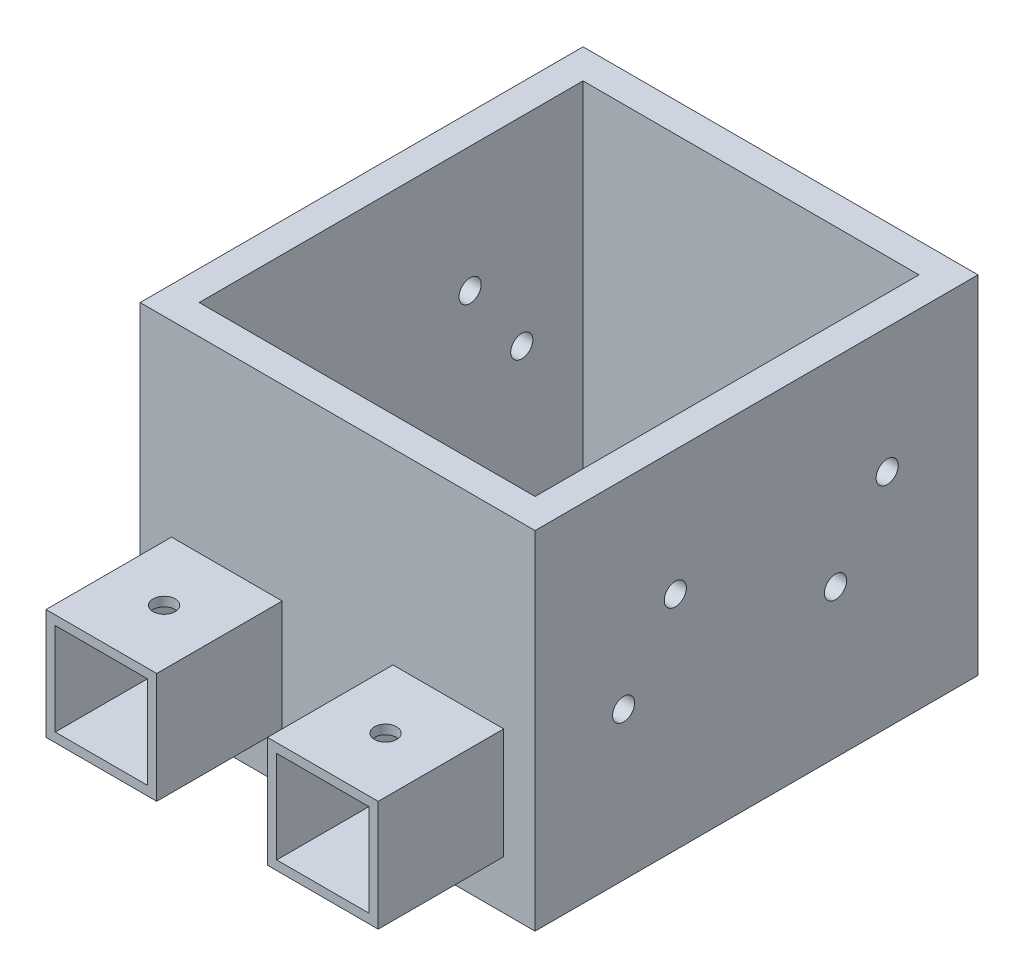
SolidWorks part; units mm, degrees
ref_plane "Front Plane" through (0, 0, 0) normal (0, 0, 1) x (1, 0, 0)
ref_plane "Top Plane" through (0, 0, 0) normal (0, 1, 0) x (1, 0, 0)
ref_plane "Right Plane" through (0, 0, 0) normal (1, 0, 0) x (0, 0, -1)
sketch "Sketch1" plane through (0, 0, 0) normal (0, 1, 0) x (1, 0, 0)
  line L1 (-26.75, 30) -> (26.75, 30)
  line L2 (-26.75, 30) -> (-26.75, -30)
  line L3 (-26.75, -30) -> (26.75, -30)
  line L4 (26.75, 30) -> (26.75, -30)
  line L5 (-26.75, 30) -> (26.75, -30) construction
  line L6 (-26.75, -30) -> (26.75, 30) construction
  line L7 (-22.75, 26) -> (22.75, 26)
  line L8 (-22.75, 26) -> (-22.75, -26)
  line L9 (-22.75, -26) -> (22.75, -26)
  line L10 (22.75, 26) -> (22.75, -26)
  line L11 (-22.75, 26) -> (22.75, -26) construction
  line L12 (-22.75, -26) -> (22.75, 26) construction
  point P0 (0, 0)
  point P6 (0, 0)
  dimension "D1" = 45.5
  dimension "D2" = 4
  dimension "D3" = 4
extrude "Boss-Extrude1" add sketch "Sketch1" along normal blind 47
sketch "Sketch3" plane through (-26.75, 0, 0) normal (-1, 0, 0) x (0, 0, 1)
  line L0 (-30, 47) -> (30, 47) construction
  circle A0 centre (18, 30.05) radius 1.5
  circle A1 centre (11, 20.05) radius 1.5
  dimension "D1" = 3
  dimension "D3" = 3
  dimension "D2" = 16.95
  dimension "D4" = 10
  dimension "D5" = 7
  dimension "D6" = 8
extrude "Cut-Extrude1" cut sketch "Sketch3" against normal blind 4 and the other way through all
pattern_linear "LPattern1" count 2 spacing 28.7 along (0, 0, -1) of "Cut-Extrude1"
sketch "Sketch4" plane through (26.75, 0, 0) normal (1, 0, 0) x (0, 0, -1)
  line L0 (-30, 47) -> (30, 47) construction
  circle A0 centre (-11, 30.05) radius 1.5
  circle A1 centre (-18, 20.05) radius 1.5
  dimension "D1" = 3
  dimension "D2" = 3
  dimension "D3" = 10
  dimension "D4" = 7
  dimension "D5" = 16.95
  dimension "D6" = 8
extrude "Cut-Extrude2" cut sketch "Sketch4" against normal blind 4
pattern_linear "LPattern2" count 2 spacing 28.7 along (0, 0, -1) of "Cut-Extrude2"
sketch "Sketch5" plane through (0, 0, 30) normal (0, 0, 1) x (1, 0, 0)
  line L0 (26.75, 47) -> (26.75, 0) construction
  line L1 (-22.5, 21.61) -> (-7.5, 21.61)
  line L2 (-22.5, 21.61) -> (-22.5, 6.61)
  line L3 (-22.5, 6.61) -> (-7.5, 6.61)
  line L4 (-7.5, 21.61) -> (-7.5, 6.61)
  line L5 (-22.5, 21.61) -> (-7.5, 6.61) construction
  line L6 (-22.5, 6.61) -> (-7.5, 21.61) construction
  line L7 (7.5, 21.61) -> (22.5, 21.61)
  line L8 (7.5, 21.61) -> (7.5, 6.61)
  line L9 (7.5, 6.61) -> (22.5, 6.61)
  line L10 (22.5, 21.61) -> (22.5, 6.61)
  line L11 (7.5, 21.61) -> (22.5, 6.61) construction
  line L12 (7.5, 6.61) -> (22.5, 21.61) construction
  line L13 (-26.75, 0) -> (26.75, 0) construction
  line L14 (-26.75, 47) -> (-26.75, 0) construction
  line L15 (8.75, 20.36) -> (21.25, 20.36)
  line L17 (8.75, 20.36) -> (8.75, 7.86)
  line L18 (8.75, 7.86) -> (21.25, 7.86)
  line L19 (21.25, 20.36) -> (21.25, 7.86)
  line L20 (8.75, 20.36) -> (21.25, 7.86) construction
  line L21 (8.75, 7.86) -> (21.25, 20.36) construction
  line L22 (-21.25, 20.36) -> (-8.75, 20.36)
  line L23 (-21.25, 20.36) -> (-21.25, 7.86)
  line L24 (-21.25, 7.86) -> (-8.75, 7.86)
  line L25 (-8.75, 20.36) -> (-8.75, 7.86)
  line L26 (-21.25, 20.36) -> (-8.75, 7.86) construction
  line L27 (-21.25, 7.86) -> (-8.75, 20.36) construction
  point P0 (-15, 14.11)
  point P5 (15, 14.11)
  point P16 (-15, 14.11)
  point P18 (15, 14.11)
  dimension "D1" = 4.25
  dimension "D2" = 4.25
  dimension "D3" = 15
  dimension "D5" = 12.5
  dimension "D4" = 6.61
extrude "Boss-Extrude2" add sketch "Sketch5" along normal blind 17
sketch "Sketch6" plane through (0, 21.61, 0) normal (0, 1, 0) x (1, 0, 0)
  line L1 (-7.5, -47) -> (-7.5, -30) construction
  line L2 (-7.5, -47) -> (-22.5, -47) construction
  line L3 (22.5, -47) -> (22.5, -30) construction
  line L4 (22.5, -47) -> (7.5, -47) construction
  circle A0 centre (-15, -38.5) radius 1.5
  circle A1 centre (15, -38.5) radius 1.5
  point P6 (-7.5, -38.5)
  point P11 (-15, -47)
  point P14 (22.5, -38.5)
  point P18 (15, -47)
  dimension "D1" = 3
  dimension "D2" = 3
extrude "Cut-Extrude3" cut sketch "Sketch6" against normal through all
equation "\"var1\"=4.25"
equation "\"D1@Sketch5\"=\"var1\""
equation "\"D2@Sketch5\"=\"var1\""
